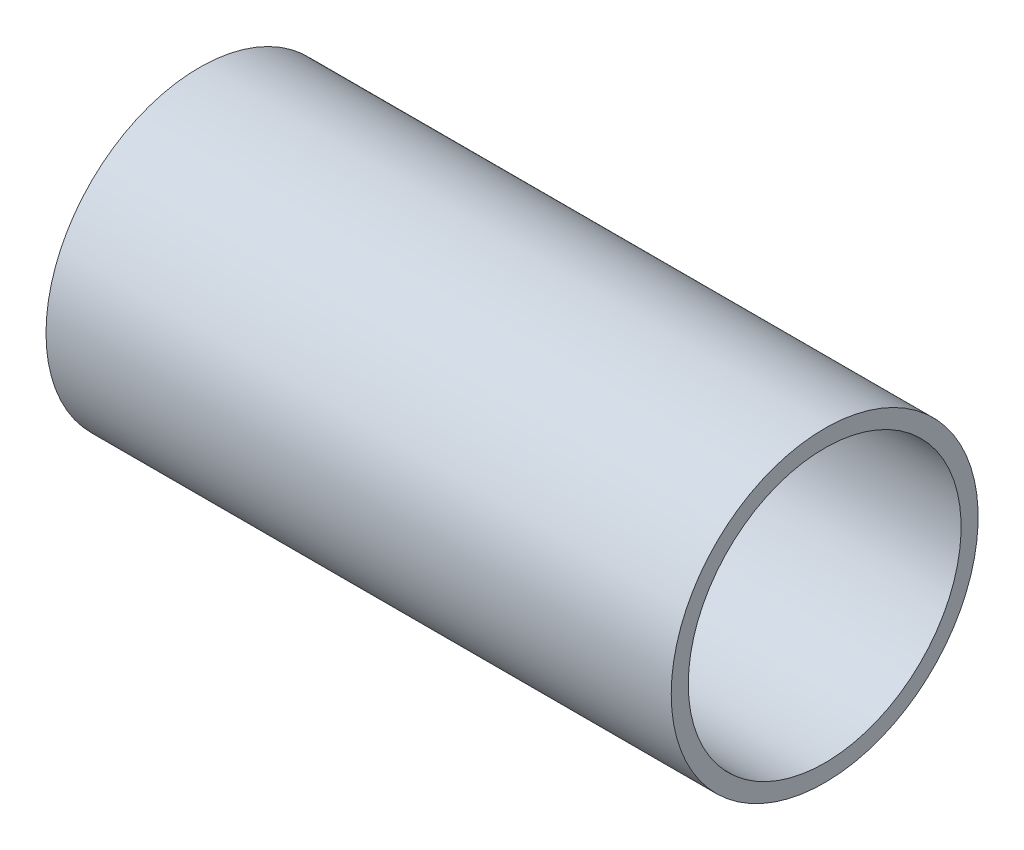
SolidWorks part; units mm, degrees
ref_plane "Front Plane" through (0, 0, 0) normal (0, 0, 1) x (1, 0, 0)
ref_plane "Top Plane" through (0, 0, 0) normal (0, 1, 0) x (1, 0, 0)
ref_plane "Right Plane" through (0, 0, 0) normal (1, 0, 0) x (0, 0, -1)
sketch "Axial profile (mm)" plane through (0, 0, 0) normal (0, 0, 1) x (1, 0, 0)
  line L0 (-110, 0) -> (75, 0) construction
  line L1 (25.7, 24) -> (135.7, 24)
  line L2 (135.7, 24) -> (135.7, 27)
  line L3 (135.7, 27) -> (25.7, 27)
  line L4 (25.7, 27) -> (25.7, 24)
revolve "Full revolution" add sketch "Axial profile (mm)" angle 360 about L0
